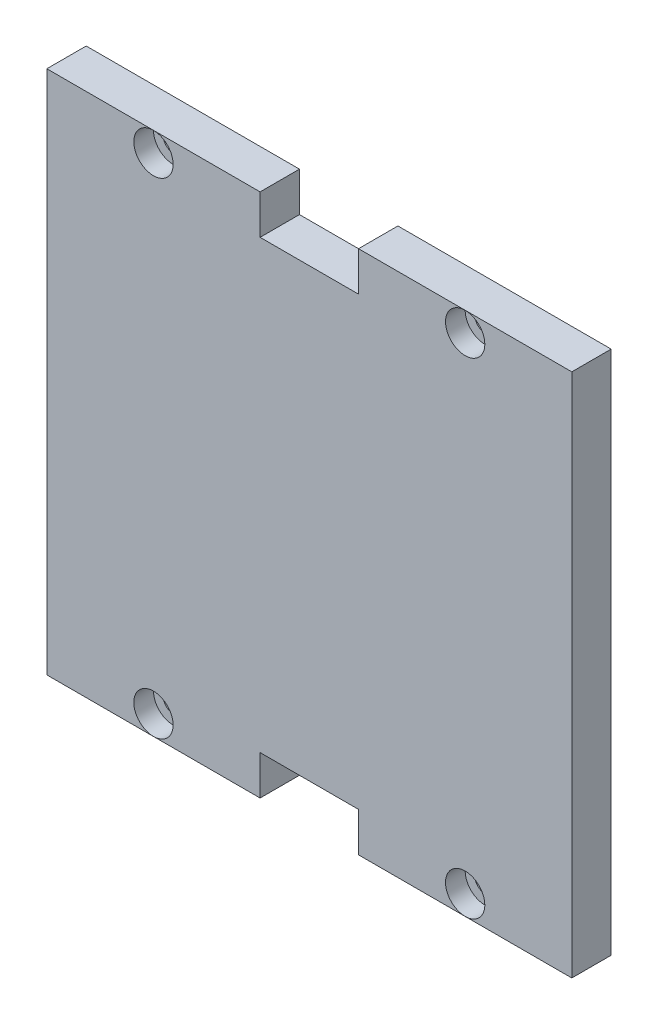
SolidWorks part; units mm, degrees
ref_plane "Plan de face" through (0, 0, 0) normal (0, 0, 1) x (1, 0, 0)
ref_plane "Plan de dessus" through (0, 0, 0) normal (0, 1, 0) x (1, 0, 0)
ref_plane "Plan de droite" through (0, 0, 0) normal (1, 0, 0) x (0, 0, -1)
sketch "Esquisse1" plane through (0, 0, 0) normal (0, 0, 1) x (1, 0, 0)
  line L1 (0, 0) -> (-80, 0)
  line L2 (0, 0) -> (0, 80)
  line L3 (0, 80) -> (-80, 80)
  line L4 (-80, 0) -> (-80, 80)
  dimension "D1" = 80
  dimension "D2" = 80
extrude "Boss.-Extru.1" add sketch "Esquisse1" along normal blind 6
sketch "Esquisse2" plane through (0, 0, 6) normal (0, 0, 1) x (1, 0, 0)
  line L0 (-80, 0) -> (0, 0) construction
  line L1 (-47.5, 0) -> (-32.5, 0)
  line L2 (-47.5, 0) -> (-47.5, 6)
  line L3 (-47.5, 6) -> (-32.5, 6)
  line L4 (-32.5, 0) -> (-32.5, 6)
  line L5 (-80, 80) -> (-80, 0) construction
  line L6 (-80, 40) -> (0, 40) construction
  line L8 (-47.5, 80) -> (-32.5, 80)
  line L9 (-32.5, 80) -> (-32.5, 74)
  line L10 (-47.5, 74) -> (-32.5, 74)
  line L11 (-47.5, 80) -> (-47.5, 74)
  line L12 (0, 0) -> (0, 80) construction
  circle A0 centre (-16.25, 3) radius 1.5
  circle A1 centre (-63.75, 77) radius 1.5
  circle A2 centre (-16.25, 77) radius 1.5
  circle A3 centre (-63.75, 3) radius 1.5
  dimension "D4" = 3
  dimension "D5" = 3
  dimension "D6" = 3
  dimension "D7" = 3
  dimension "D8" = 16.25
  dimension "D9" = 16.25
  dimension "D1" = 6
  dimension "D2" = 15
  dimension "D3" = 32.5
extrude "Enlèv. mat.-Extru.1" cut sketch "Esquisse2" against normal blind 6
sketch "Esquisse3" plane through (0, 0, 6) normal (0, 0, 1) x (1, 0, 0)
  circle A0 centre (-16.25, 3) radius 2.995
  circle A1 centre (-63.75, 3) radius 2.995
  circle A2 centre (-16.25, 77) radius 2.995
  circle A3 centre (-63.75, 77) radius 2.995
  dimension "D1" = 5.99
  dimension "D2" = 5.99
  dimension "D3" = 5.99
  dimension "D4" = 5.99
extrude "Enlèv. mat.-Extru.2" cut sketch "Esquisse3" against normal blind 3
